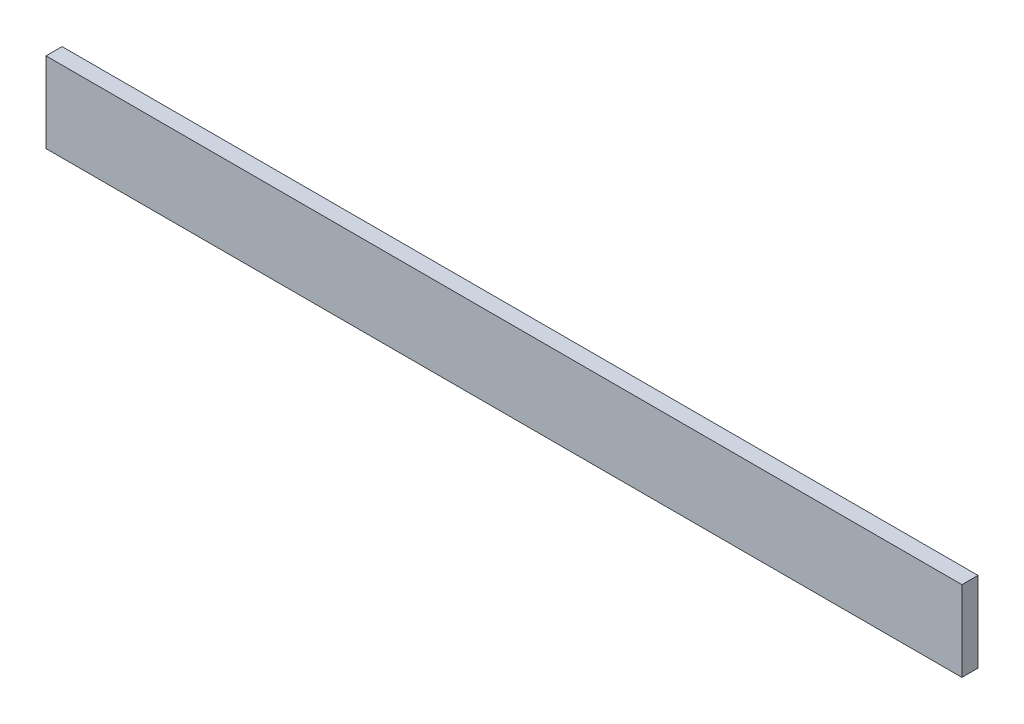
SolidWorks part; units mm, degrees
ref_plane "Front Plane" through (0, 0, 0) normal (0, 0, 1) x (1, 0, 0)
ref_plane "Top Plane" through (0, 0, 0) normal (0, 1, 0) x (1, 0, 0)
ref_plane "Right Plane" through (0, 0, 0) normal (1, 0, 0) x (0, 0, -1)
sketch "Sketch2" plane through (0, 0, 0) normal (0, 0, 1) x (1, 0, 0)
  line L1 (0, 0) -> (723.9, 0)
  line L2 (0, 0) -> (0, 63.5)
  line L3 (0, 63.5) -> (723.9, 63.5)
  line L4 (723.9, 0) -> (723.9, 63.5)
  dimension "D1" = 723.9
  dimension "D2" = 63.5
extrude "Boss-Extrude1" add sketch "Sketch2" along normal blind 12.7
